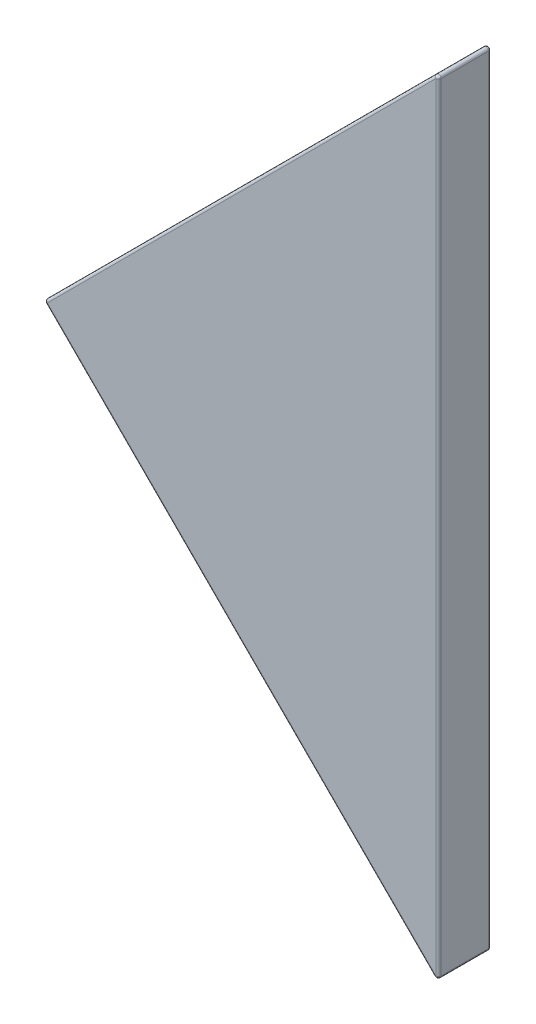
SolidWorks part; units mm, degrees
ref_plane "前视基准面" through (0, 0, 0) normal (0, 0, 1) x (1, 0, 0)
ref_plane "上视基准面" through (0, 0, 0) normal (0, 1, 0) x (1, 0, 0)
ref_plane "右视基准面" through (0, 0, 0) normal (1, 0, 0) x (0, 0, -1)
sketch "草图1" plane through (0, 0, 0) normal (0, 0, 1) x (1, 0, 0)
  line L35 (0, 0) -> (0, 150)
  line L36 (-75, 75) -> (0, 150)
  line L37 (-75, 75) -> (0, 0)
  dimension "D2" = 45
  dimension "D11" = 150
extrude "凸台-拉伸1" add sketch "草图1" along normal blind 10
fillet "圆角1" radius 0.5 9 edges at (-75, 75, 5) (0, 0, 5) (0, 150, 5) (0, 75, 10) (-37.5, 37.5, 10) (-37.5, 112.5, 10) (0, 75, 0) (-37.5, 37.5, 0) (-37.5, 112.5, 0)
